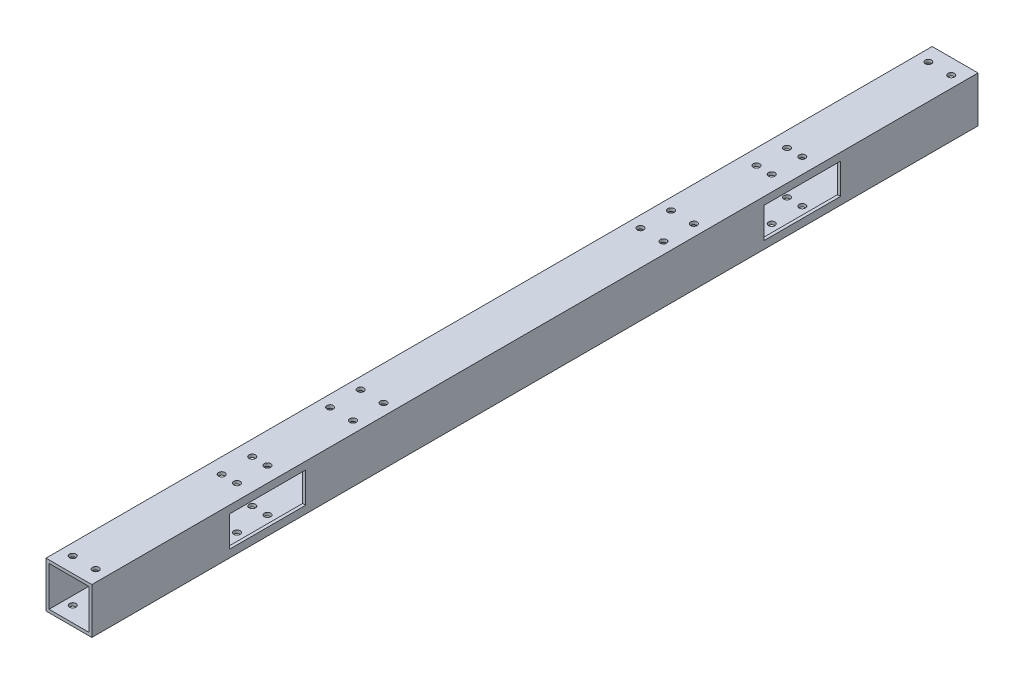
SolidWorks part; units mm, degrees
material "1060 合金"
ref_plane "前视基准面" through (0, 0, 0) normal (0, 0, 1) x (1, 0, 0)
ref_plane "上视基准面" through (0, 0, 0) normal (0, 1, 0) x (1, 0, 0)
ref_plane "右视基准面" through (0, 0, 0) normal (1, 0, 0) x (0, 0, -1)
sketch "草图1" plane through (0, 0, 0) normal (0, 0, 1) x (1, 0, 0)
  line L1 (-15, -15) -> (15, -15)
  line L2 (-15, -15) -> (-15, 15)
  line L3 (-15, 15) -> (15, 15)
  line L4 (15, -15) -> (15, 15)
  line L5 (-15, -15) -> (15, 15) construction
  line L6 (-15, 15) -> (15, -15) construction
  line L7 (-13, -13) -> (13, -13)
  line L8 (-13, -13) -> (-13, 13)
  line L9 (-13, 13) -> (13, 13)
  line L10 (13, -13) -> (13, 13)
  line L11 (-13, -13) -> (13, 13) construction
  line L12 (-13, 13) -> (13, -13) construction
  point P0 (0, 0)
  point P6 (0, 0)
  dimension "D1" = 30
  dimension "D2" = 30
  dimension "D3" = 2
extrude "凸台-拉伸1" add sketch "草图1" along normal blind 580
sketch "草图2" plane through (-15, 0, 0) normal (-1, 0, 0) x (0, 0, 1)
  line L0 (580, 15) -> (0, 15) construction
  line L1 (90, 10) -> (140, 10)
  line L2 (90, 10) -> (90, -10)
  line L3 (90, -10) -> (140, -10)
  line L4 (140, 10) -> (140, -10)
  line L5 (0, 15) -> (0, -15) construction
  line L6 (290, 138.5186) -> (290, -108.5186) construction
  line L7 (490, -10) -> (440, -10)
  line L8 (440, 10) -> (440, -10)
  line L9 (490, 10) -> (440, 10)
  line L10 (490, 10) -> (490, -10)
  point P11 (290, 15)
  dimension "D1" = 20
  dimension "D2" = 50
  dimension "D3" = 5
  dimension "D4" = 90
extrude "切除-拉伸1" cut sketch "草图2" against normal through all
sketch "草图3" plane through (0, 15, 0) normal (0, 1, 0) x (1, 0, 0)
  circle A0 centre (7.5, -10) radius 2.1
  circle A1 centre (-7.5, -10) radius 2.1
  circle A6 centre (-7.5, -570) radius 2.1
  circle A7 centre (7.5, -570) radius 2.1
extrude "切除-拉伸2" cut sketch "草图3" against normal through all
sketch "草图4" plane through (0, 15, 0) normal (0, 1, 0) x (1, 0, 0)
  line L0 (15, -580) -> (15, 0) construction
  line L1 (-15, -580) -> (-15, 0) construction
  line L2 (103.2815, -290) -> (-73.2815, -290) construction
  line L3 (85, -1217.7161) -> (85, 57.7161) construction
  circle A0 centre (7.5, -401.5675) radius 2.1
  circle A1 centre (-7.5, -401.5675) radius 2.1
  circle A2 centre (-7.5, -381.5675) radius 2.1
  circle A3 centre (7.5, -381.5675) radius 2.1
  circle A4 centre (7.5, -178.4325) radius 2.1
  circle A5 centre (-7.5, -178.4325) radius 2.1
  circle A6 centre (-7.5, -198.4325) radius 2.1
  circle A7 centre (7.5, -198.4325) radius 2.1
  circle A8 centre (162.5, -178.4325) radius 2.1
  circle A9 centre (177.5, -178.4325) radius 2.1
  circle A10 centre (177.5, -198.4325) radius 2.1
  circle A11 centre (162.5, -198.4325) radius 2.1
  circle A12 centre (162.5, -381.5675) radius 2.1
  circle A13 centre (162.5, -401.5675) radius 2.1
  circle A14 centre (177.5, -401.5675) radius 2.1
  circle A15 centre (177.5, -381.5675) radius 2.1
  point P11 (85, -580)
  point P19 (15, -290)
  dimension "D1" = 4.2
  dimension "D2" = 7.5
  dimension "D3" = 7.5
  dimension "D4" = 20
extrude "切除-拉伸3" cut sketch "草图4" against normal through all
sketch "草图6" plane through (15, 0, 0) normal (1, 0, 0) x (0, 0, -1)
  line L0 (-490, 10) -> (-490, 15)
  line L1 (-580, 15) -> (0, 15) construction
sketch "草图7" plane through (0, 15, 0) normal (0, 1, 0) x (1, 0, 0)
  line L0 (15, -490) -> (-15, -490)
  line L1 (-15, -580) -> (-15, 0) construction
  line L2 (15, -490) -> (15, -440)
  line L3 (15, -580) -> (15, 0) construction
  circle A0 centre (5, -455) radius 2.1
  circle A1 centre (-5, -455) radius 2.1
  circle A2 centre (-5, -475) radius 2.1
  circle A3 centre (5, -475) radius 2.1
  point P5 (15, -465)
  point P13 (5, -465)
  point P15 (-5, -465)
  point P16 (5, -455)
  point P17 (5, -475)
  point P18 (-5, -455)
  point P19 (-5, -475)
  dimension "D10" = 4.2
  dimension "D11" = 4.2
  dimension "D12" = 4.2
  dimension "D13" = 4.2
  dimension "D1" = 50
  dimension "D4" = 10
  dimension "D5" = 10
  dimension "D6" = 10
  dimension "D7" = 10
  dimension "D8" = 10
  dimension "D9" = 10
extrude "切除-拉伸4" cut sketch "草图7" against normal through all contours A2 | A3 | A0 | A1 | L2 L0
sketch "草图8" plane through (0, -15, 0) normal (0, -1, 0) x (1, 0, 0)
  line L0 (-15, 580) -> (-15, 0)
  line L1 (-15, 290) -> (15, 290)
  line L2 (15, 580) -> (15, 0) construction
  point P4 (-15, 290)
sketch "草图9" plane through (-15, 0, 0) normal (-1, 0, 0) x (0, 0, 1)
  line L0 (290, -15) -> (290, 15)
  line L1 (580, 15) -> (0, 15) construction
ref_plane "基准面1" through (0, 0, 290) normal (0, 0, -1) x (-1, 0, 0)
mirror "镜向1" about plane through (0, 0, 290) normal (0, 0, -1) of "切除-拉伸4"
